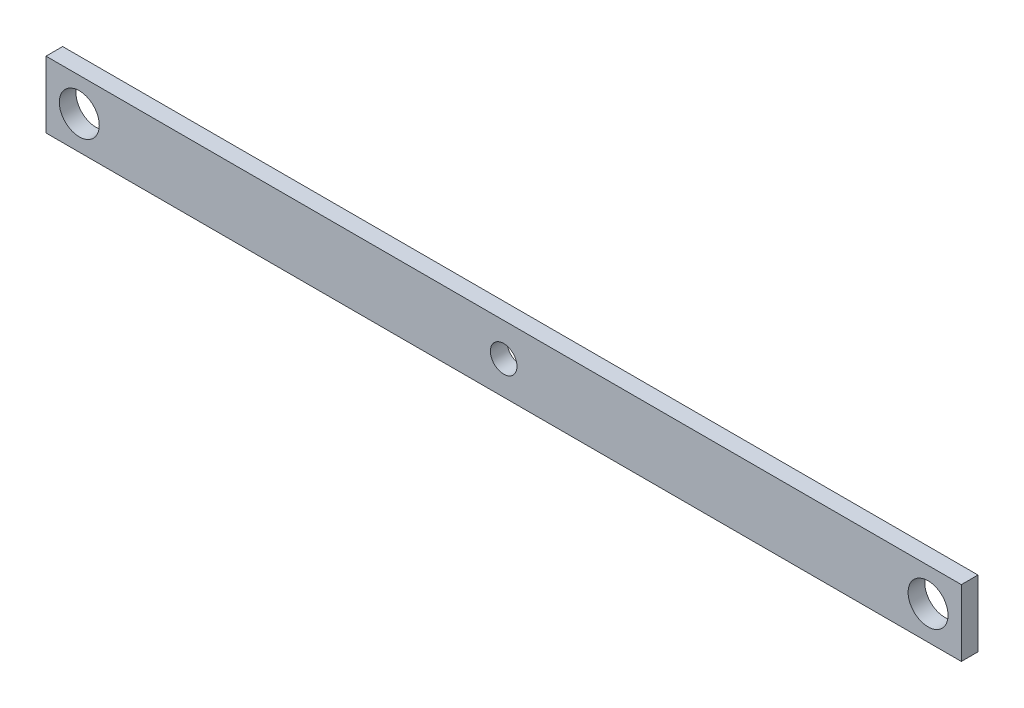
SolidWorks part; units mm, degrees
ref_plane "前视基准面" through (0, 0, 0) normal (0, 0, 1) x (1, 0, 0)
ref_plane "上视基准面" through (0, 0, 0) normal (0, 1, 0) x (1, 0, 0)
ref_plane "右视基准面" through (0, 0, 0) normal (1, 0, 0) x (0, 0, -1)
sketch "草图1" plane through (0, 0, 0) normal (0, 0, 1) x (1, 0, 0)
  line L1 (-137.5, 10) -> (137.5, 10)
  line L2 (-137.5, 10) -> (-137.5, -10)
  line L3 (-137.5, -10) -> (137.5, -10)
  line L4 (137.5, 10) -> (137.5, -10)
  line L5 (-137.5, 10) -> (137.5, -10) construction
  line L6 (-137.5, -10) -> (137.5, 10) construction
  circle A0 centre (0, 0) radius 4
  circle A1 centre (-127.5, 0) radius 6
  circle A2 centre (127.5, 0) radius 6
  point P0 (0, 0)
  dimension "D3" = 8
  dimension "D4" = 12
  dimension "D6" = 12
  dimension "D1" = 275
  dimension "D2" = 20
  dimension "D5" = 10
  dimension "D7" = 10
extrude "凸台-拉伸1" add sketch "草图1" along normal blind 5
